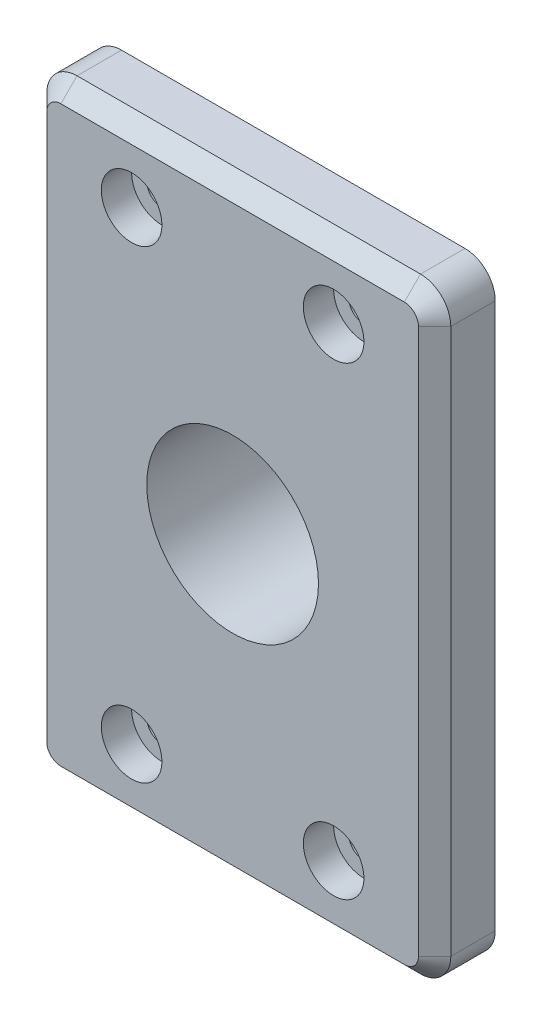
SolidWorks part; units mm, degrees
ref_plane "前基準面" through (0, 0, 0) normal (0, 0, 1) x (1, 0, 0)
ref_plane "上基準面" through (0, 0, 0) normal (0, 1, 0) x (1, 0, 0)
ref_plane "右基準面" through (0, 0, 0) normal (1, 0, 0) x (0, 0, -1)
sketch "草圖1" plane through (0, 0, 0) normal (0, 0, 1) x (1, 0, 0)
  line L0 (0, 30) -> (0, -30) construction
  line L1 (-20, 30) -> (20, 30)
  line L2 (-20, 30) -> (-20, -30)
  line L3 (-20, -30) -> (20, -30)
  line L4 (20, 30) -> (20, -30)
  line L5 (-20, 0) -> (20, 0) construction
  circle A0 centre (-10, 23) radius 1.5
  circle A1 centre (10, 23) radius 1.5
  circle A2 centre (10, -23) radius 1.5
  circle A3 centre (-10, -23) radius 1.5
  point P4 (0, 30)
  point P6 (-20, 0)
  dimension "D5" = 3
  dimension "D1" = 60
  dimension "D2" = 40
  dimension "D3" = 23
  dimension "D4" = 10
extrude "填料-伸長1" add sketch "草圖1" along normal blind 6
sketch "草圖2" plane through (0, 0, 6) normal (0, 0, 1) x (1, 0, 0)
  circle A0 centre (-10, 23) radius 3
  circle A1 centre (10, 23) radius 3
  circle A2 centre (10, -23) radius 3
  circle A3 centre (-10, -23) radius 3
  dimension "D1" = 6
  dimension "D2" = 6
  dimension "D3" = 6
  dimension "D4" = 6
extrude "除料-伸長1" cut sketch "草圖2" against normal blind 3
fillet "圓角1" radius 3 4 edges at (-20, -30, 3) (20, -30, 3) (-20, 30, 3) (20, 30, 3)
chamfer "導角1" distance 1.6 angle 45 8 edges at (-20, 0, 6) (-19.1213, -29.1213, 6) (-19.1213, 29.1213, 6) (0, -30, 6) (0, 30, 6) (19.1213, -29.1213, 6) (19.1213, 29.1213, 6) (20, 0, 6)
sketch "草圖3" plane through (0, 0, 6) normal (0, 0, 1) x (1, 0, 0)
  circle A0 centre (0, 0) radius 8.5
  dimension "D1" = 17
extrude "除料-伸長2" cut sketch "草圖3" against normal through all
sketch "草圖4" plane through (0, 0, 0) normal (0, 0, -1) x (-1, 0, 0)
  circle A0 centre (0, 0) radius 8.5
  circle A1 centre (0, 0) radius 11.5
  dimension "D1" = 23
extrude "填料-伸長2" add sketch "草圖4" along normal blind 6
